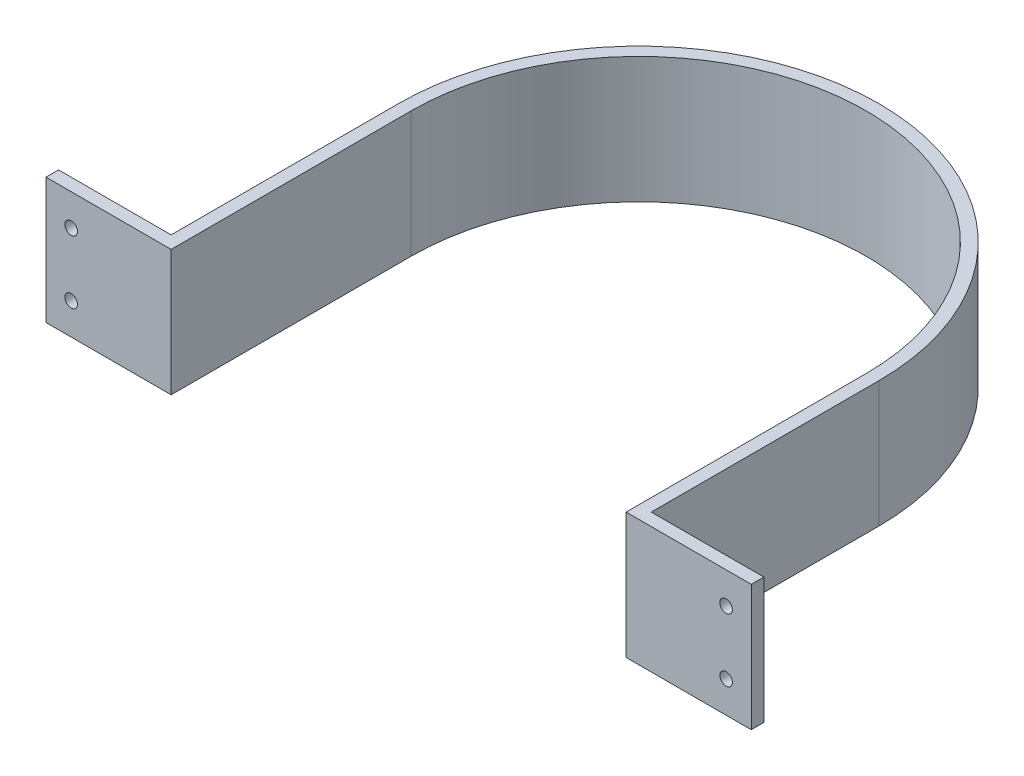
SolidWorks part; units mm, degrees
other "Markup1"
sketch "Sketch14" plane through (-178.835, 31.75, 121.05) normal (-0.0444, 0.3923, 0.9187) x (0.9976, 0.0664, 0.0198)
ref_plane "Front Plane" through (0, 0, 0) normal (0, 0, 1) x (1, 0, 0)
ref_plane "Top Plane" through (0, 0, 0) normal (0, 1, 0) x (1, 0, 0)
ref_plane "Right Plane" through (0, 0, 0) normal (1, 0, 0) x (0, 0, -1)
sketch "Sketch1" plane through (0, 0, 0) normal (0, 1, 0) x (1, 0, 0)
  line L0 (0, 0) -> (-121.05, 0) construction
  line L1 (0, 0) -> (0, -121.05) construction
  line L2 (0, -121.05) -> (-177.8, -121.05)
  line L3 (-114.7, 0) -> (-114.7, -121.05)
  line L4 (-121.05, 0) -> (-121.05, -121.05)
  line L5 (0, -114.7) -> (-177.8, -114.7)
  line L6 (-177.8, -114.7) -> (-177.8, -121.05)
  line L7 (-120.3819, -12.7) -> (-121.05, -12.7)
  line L8 (177.8, -114.7) -> (177.8, -121.05)
  line L9 (0, -114.7) -> (177.8, -114.7)
  line L10 (-113.9947, -12.7) -> (-114.7, -12.7)
  line L11 (121.05, 0) -> (121.05, -121.05)
  line L12 (114.7, 0) -> (114.7, -121.05)
  line L13 (0, -121.05) -> (177.8, -121.05)
  circle A0 centre (0, 0) radius 102
  circle A1 centre (0, 0) radius 114.7
  arc A3 (-114.7, -38.6912) -> (-121.05, 0) centre (0, 0) ccw
  arc A4 (-114.7, -38.6912) -> (119.5416, -19.05) centre (0, 0) ccw
  arc A5 (120.3819, -12.7) -> (120.3819, 12.7) centre (0, 0) ccw
  circle A6 centre (0, 0) radius 121.05 construction
  point P8 (-177.8, -117.875)
  point P29 (0, 0)
  dimension "D1" = 204
  dimension "D2" = 12.7
  dimension "D4" = 177.8
  dimension "D3" = 6.35
  dimension "D5" = 6.35
extrude "Boss-Extrude1" add sketch "Sketch1" along normal mid plane 63.5
sketch "Sketch3" plane through (0, 0, 121.05) normal (0, 0, 1) x (1, 0, 0)
  line L0 (-152.4, 31.75) -> (-152.4, -31.75) construction
  line L1 (-177.8, 31.75) -> (-177.8, -31.75) construction
  line L3 (-114.7, 31.75) -> (-177.8, 31.75) construction
  line L4 (-155.575, 31.75) -> (-155.575, -31.75) construction
  line L5 (-114.7, -31.75) -> (-177.8, -31.75) construction
  line L6 (-122.955, 31.75) -> (-122.955, -31.75) construction
  line L7 (0, 0) -> (0, 31.75) construction
  line L8 (114.7, 31.75) -> (-114.7, 31.75) construction
  line L9 (-174.625, 31.75) -> (-174.625, -31.75)
  line L10 (-114.7, 31.75) -> (-114.7, -31.75) construction
  line L11 (-174.625, 31.75) -> (-174.625, -31.75) construction
  line L12 (-155.575, 0) -> (-174.625, 0) construction
  line L13 (-165.1, 0) -> (-165.1, 31.75) construction
  circle A8 centre (-165.1, 15.875) radius 3.175
  circle A9 centre (-165.1, -15.875) radius 3.175
  circle A10 centre (165.1, -15.875) radius 3.175
  circle A11 centre (165.1, 15.875) radius 3.175
  dimension "D2" = 8.255
  dimension "D1" = 25.4
  dimension "D3" = 3.175
  dimension "D4" = 3.175
extrude "Cut-Extrude2" cut sketch "Sketch3" against normal up to surface (6.35 mm away) up to face at (-149.425, 0, 114.7)
